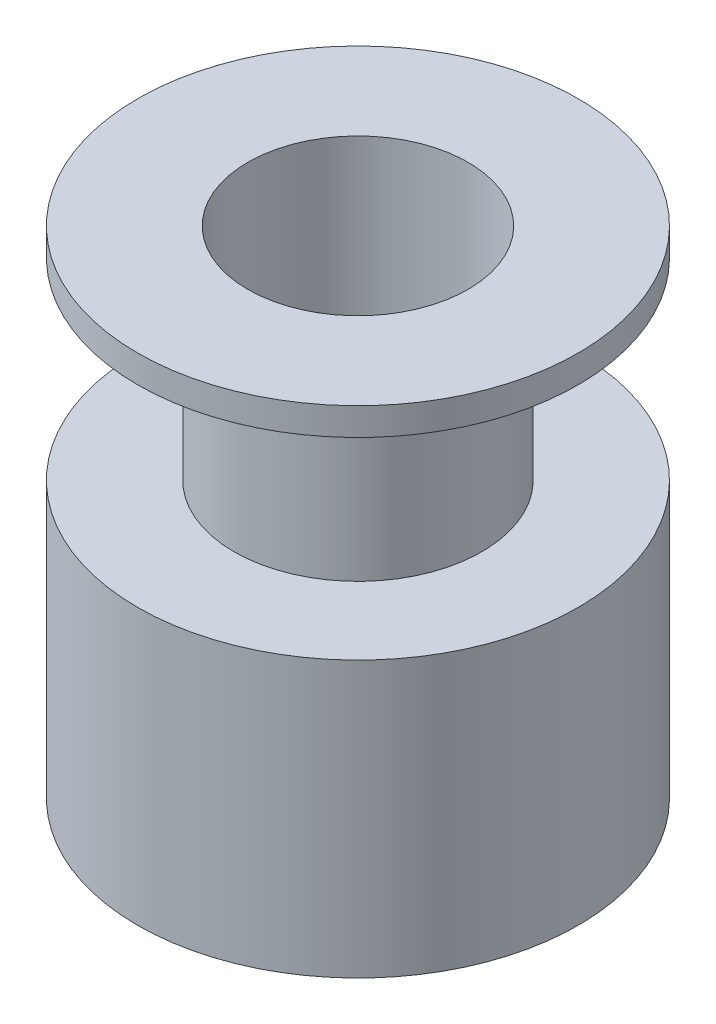
SolidWorks part; units mm, degrees
ref_plane "Front Plane" through (0, 0, 0) normal (0, 0, 1) x (1, 0, 0)
ref_plane "Top Plane" through (0, 0, 0) normal (0, 1, 0) x (1, 0, 0)
ref_plane "Right Plane" through (0, 0, 0) normal (1, 0, 0) x (0, 0, -1)
sketch "Sketch1" plane through (0, 0, 0) normal (0, 1, 0) x (1, 0, 0)
  circle A0 centre (0, 0) radius 8
  dimension "D1" = 16
extrude "Boss-Extrude1" add sketch "Sketch1" along normal blind 18
sketch "Sketch2" plane through (0, 18, 0) normal (0, 1, 0) x (1, 0, 0)
  circle A1 centre (0, 0) radius 4
  dimension "D1" = 8
extrude "Cut-Extrude1" cut sketch "Sketch2" against normal through all
sketch "Sketch3" plane through (0, 18, 0) normal (0, 1, 0) x (1, 0, 0)
  circle A0 centre (0, 0) radius 8
  circle A1 centre (0, 0) radius 4.5
  dimension "D1" = 9
  dimension "D2" = 16
extrude "Cut-Extrude2" cut sketch "Sketch3" against normal blind 7 from offset 1
